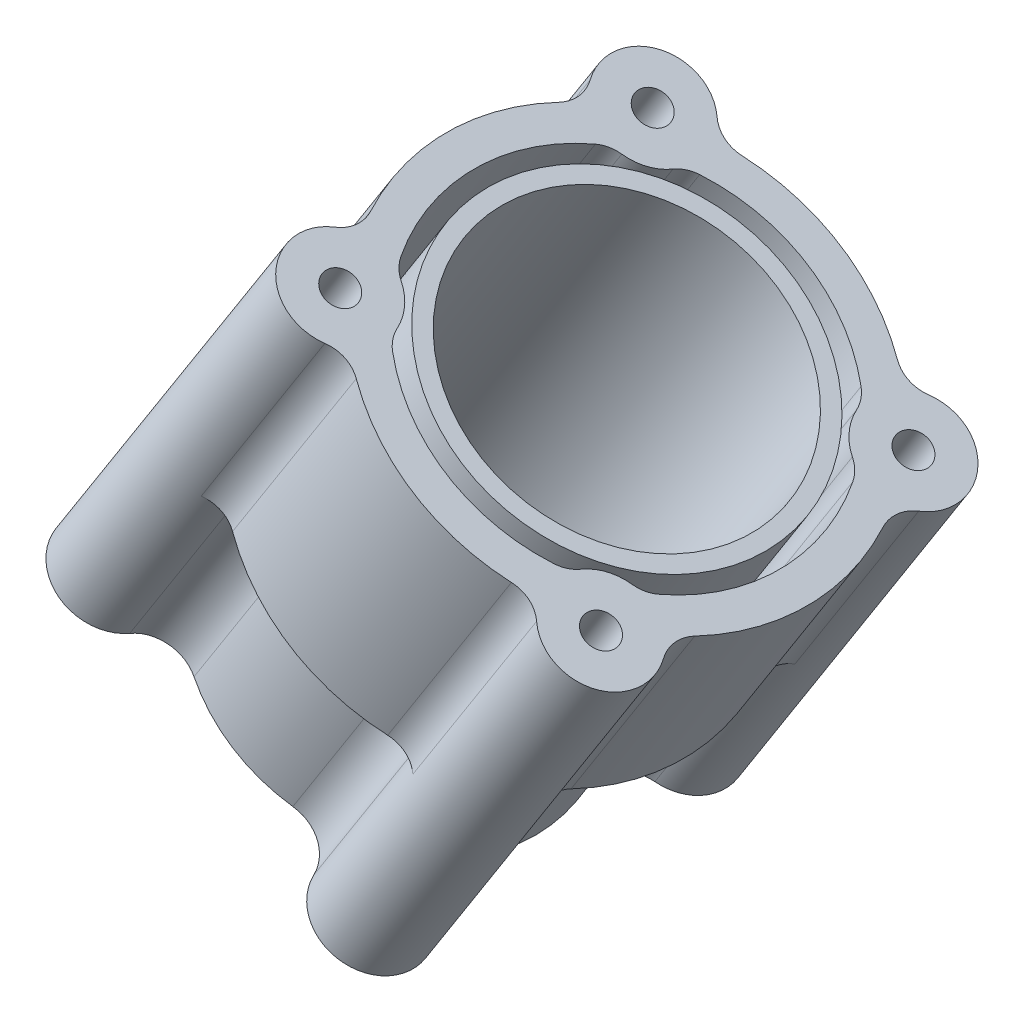
SolidWorks part; units mm, degrees
ref_plane "Front Plane" through (0, 0, 0) normal (0, 0, 1) x (1, 0, 0)
ref_plane "Top Plane" through (0, 0, 0) normal (0, 1, 0) x (1, 0, 0)
ref_plane "Right Plane" through (0, 0, 0) normal (1, 0, 0) x (0, 0, -1)
sketch "Sketch1" plane through (0, 0, 0) normal (1, 0, 0) x (0, 0, -1)
  line L0 (-30, 0) -> (30, 0) construction
  point P4 (0, 0)
  dimension "D1" = 60
ref_plane "Plane1" through (0, 0, 0) normal (0.5373, 0.8434, 0) x (0, 0, -1)
sketch "Sketch2" plane through (0, 0, 0) normal (0.5373, 0.8434, 0) x (0, 0, -1)
  line L0 (0, 0) -> (237.5, 0) construction
  line L1 (237.5, 0) -> (237.5, 65) construction
  circle A0 centre (237.5, 0) radius 45
  circle A1 centre (237.5, 0) radius 50
  arc A2 (190.8197, 29.0852) -> (190.8197, -29.0852) centre (237.5, 0) ccw
  arc A3 (178.8254, 27.9695) -> (178.8254, -27.9695) centre (237.5, 0) ccw
  arc A4 (198.7078, 59.2137) -> (177.8791, 38.1635) centre (190, 47) ccw
  circle A5 centre (190, 47) radius 5
  circle A6 centre (285, 47) radius 5
  arc A7 (276.2922, 59.2137) -> (297.1209, 38.1635) centre (285, 47) cw
  circle A8 centre (285, -47) radius 5
  arc A9 (279.4158, -33.0782) -> (271.0199, -41.5634) centre (285, -47) ccw
  circle A10 centre (190, -47) radius 5
  arc A11 (195.5842, -33.0782) -> (203.9801, -41.5634) centre (190, -47) cw
  arc A12 (195.5842, 33.0782) -> (203.9801, 41.5634) centre (190, 47) ccw
  arc A13 (266.0888, 58.3754) -> (208.9112, 58.3754) centre (237.5, 0) ccw
  circle A14 centre (237.5, 0) radius 65 construction
  circle A15 centre (237.5, 0) radius 55 construction
  arc A16 (267.0776, 46.3699) -> (207.9224, 46.3699) centre (237.5, 0) ccw
  arc A17 (279.4158, 33.0782) -> (271.0199, 41.5634) centre (285, 47) cw
  arc A18 (296.1746, -27.9695) -> (296.1746, 27.9695) centre (237.5, 0) ccw
  arc A19 (284.1803, -29.0852) -> (284.1803, 29.0852) centre (237.5, 0) ccw
  arc A20 (276.2922, -59.2137) -> (297.1209, -38.1635) centre (285, -47) ccw
  arc A21 (207.9224, -46.3699) -> (267.0776, -46.3699) centre (237.5, 0) ccw
  arc A22 (208.9112, -58.3754) -> (266.0888, -58.3754) centre (237.5, 0) ccw
  arc A23 (198.7078, -59.2137) -> (177.8791, -38.1635) centre (190, -47) cw
  arc A24 (207.9224, -46.3699) -> (203.9801, -41.5634) centre (213.3002, -37.939) cw
  arc A25 (190.8197, -29.0852) -> (195.5842, -33.0782) centre (199.307, -23.797) ccw
  arc A26 (178.8254, -27.9695) -> (177.8791, -38.1635) centre (169.7985, -32.2725) cw
  arc A27 (208.9112, -58.3754) -> (198.7078, -59.2137) centre (204.513, -67.3562) ccw
  arc A28 (279.4158, -33.0782) -> (284.1803, -29.0852) centre (275.693, -23.797) ccw
  arc A29 (267.0776, -46.3699) -> (271.0199, -41.5634) centre (261.6998, -37.939) ccw
  arc A30 (276.2922, -59.2137) -> (266.0888, -58.3754) centre (270.487, -67.3562) ccw
  arc A31 (296.1746, -27.9695) -> (297.1209, -38.1635) centre (305.2015, -32.2725) ccw
  arc A32 (284.1803, 29.0852) -> (279.4158, 33.0782) centre (275.693, 23.797) ccw
  arc A33 (267.0776, 46.3699) -> (271.0199, 41.5634) centre (261.6998, 37.939) cw
  arc A34 (296.1746, 27.9695) -> (297.1209, 38.1635) centre (305.2015, 32.2725) cw
  arc A35 (266.0888, 58.3754) -> (276.2922, 59.2137) centre (270.487, 67.3562) ccw
  arc A36 (198.7078, 59.2137) -> (208.9112, 58.3754) centre (204.513, 67.3562) ccw
  arc A37 (207.9224, 46.3699) -> (203.9801, 41.5634) centre (213.3002, 37.939) ccw
  arc A38 (195.5842, 33.0782) -> (190.8197, 29.0852) centre (199.307, 23.797) ccw
  arc A39 (177.8791, 38.1635) -> (178.8254, 27.9695) centre (169.7985, 32.2725) cw
  point P9 (292.5, 0)
  point P26 (302.5, 0)
  point P45 (202.7369, -54.9229)
  point P48 (282.0166, -32.2997)
  point P57 (282.0166, 32.2997)
  dimension "D1" = 90
  dimension "D6" = 30
  dimension "D9" = 10
  dimension "D10" = 10
  dimension "D2" = 237.5
  dimension "D7" = 47
  dimension "D8" = 47.5
  dimension "D3" = 5
  dimension "D4" = 5
  dimension "D5" = 10
extrude "Boss-Extrude1" add sketch "Sketch2" along normal blind 130 from offset 100 contours A4 A39 A3 A26 A23 A27 A22 A30 A20 A31 A18 A34 A7 A35 A13 A36 A10 A8 A5 A6 A38 A12 A37 A16 A33 A17 A32 A19 A28 A9 A29 A21 A24 A11 A25 A2 | A1 A0
sketch "Sketch3" plane through (53.73, 84.3391, 0) normal (-0.5373, -0.8434, 0) x (0.8434, -0.5373, 0)
  circle A0 centre (0, -237.5) radius 50
  circle A1 centre (0, -237.5) radius 100
  dimension "D1" = 100
  dimension "D2" = 200
extrude "Cut-Extrude1" cut sketch "Sketch3" against normal blind 60
sketch "Sketch4" plane through (85.9679, 134.9426, 0) normal (-0.5373, -0.8434, 0) x (0.8434, -0.5373, 0)
  line L0 (0, 0) -> (0, -302.5) construction
  line L1 (0, -237.5) -> (-47, -190) construction
  line L2 (0, -237.5) -> (-137.0797, -237.5) construction
  arc A0 (-27.9695, -296.1746) -> (27.9695, -296.1746) centre (0, -237.5) ccw construction
  circle A1 centre (-47, -190) radius 5
  arc A2 (-33.1642, -184.206) -> (-52.9401, -203.7737) centre (-47, -190) ccw
  arc A5 (-46.5259, -219.1877) -> (-52.9401, -203.7737) centre (-57.6921, -214.7927) ccw
  arc A6 (-17.819, -190.7829) -> (-33.1642, -184.206) centre (-22.0955, -179.5708) cw
  arc A7 (-17.819, -190.7829) -> (-46.5259, -219.1877) centre (0, -237.5) ccw
  circle A8 centre (0, -237.5) radius 50 construction
  circle A9 centre (47, -190) radius 5
  arc A10 (17.819, -190.7829) -> (33.1642, -184.206) centre (22.0955, -179.5708) ccw
  arc A11 (17.819, -190.7829) -> (46.5259, -219.1877) centre (0, -237.5) cw
  arc A12 (46.5259, -219.1877) -> (52.9401, -203.7737) centre (57.6921, -214.7927) cw
  arc A13 (33.1642, -184.206) -> (52.9401, -203.7737) centre (47, -190) cw
  circle A14 centre (47, -285) radius 5
  arc A15 (17.819, -284.2171) -> (46.5259, -255.8123) centre (0, -237.5) ccw
  arc A16 (46.5259, -255.8123) -> (52.9401, -271.2263) centre (57.6921, -260.2073) ccw
  arc A17 (33.1642, -290.794) -> (52.9401, -271.2263) centre (47, -285) ccw
  arc A18 (17.819, -284.2171) -> (33.1642, -290.794) centre (22.0955, -295.4292) cw
  circle A19 centre (-47, -285) radius 5
  arc A20 (-17.819, -284.2171) -> (-33.1642, -290.794) centre (-22.0955, -295.4292) ccw
  arc A21 (-17.819, -284.2171) -> (-46.5259, -255.8123) centre (0, -237.5) cw
  arc A22 (-46.5259, -255.8123) -> (-52.9401, -271.2263) centre (-57.6921, -260.2073) cw
  arc A23 (-33.1642, -290.794) -> (-52.9401, -271.2263) centre (-47, -285) cw
  dimension "D1" = 30
  dimension "D2" = 10
  dimension "D3" = 24
  dimension "D4" = 50
extrude "Boss-Extrude3" add sketch "Sketch4" along normal up to surface (60 mm away) up to face at (15.7773, 108.5176, -237.5)
